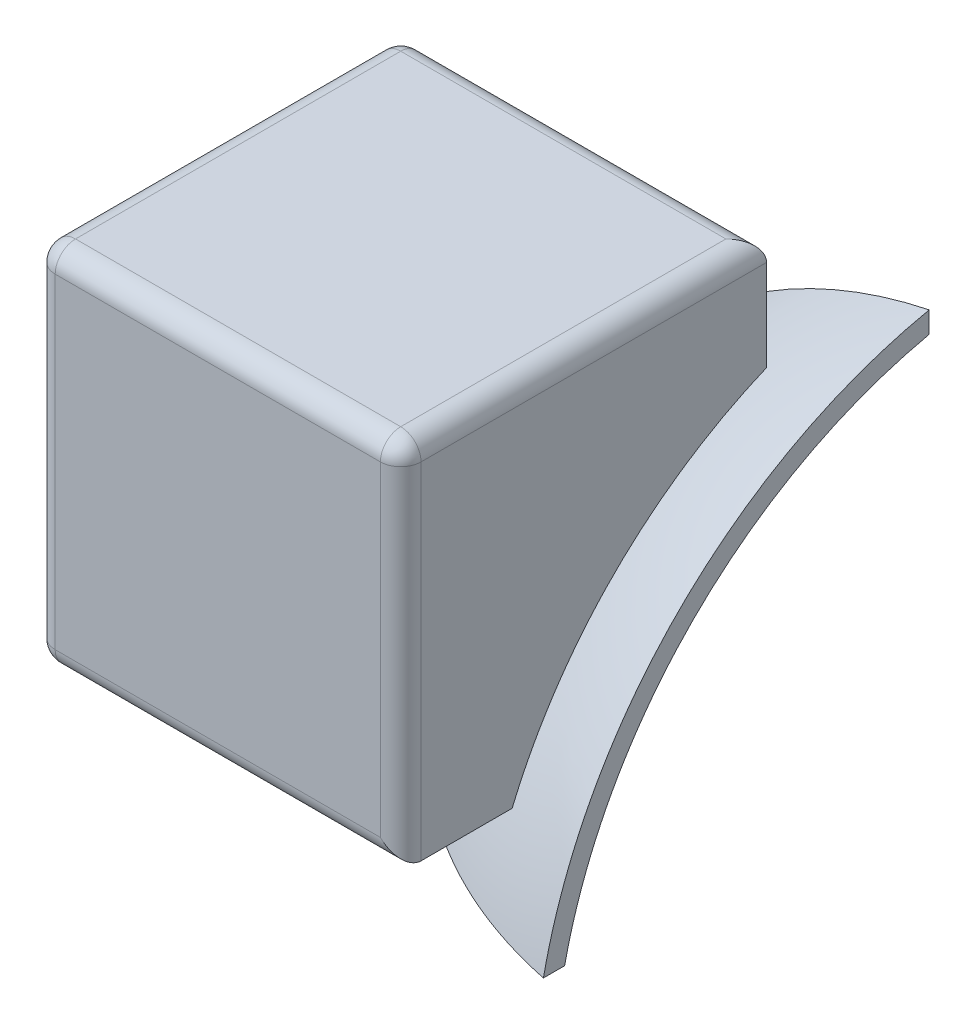
SolidWorks part; units mm, degrees
ref_plane "前视基准面" through (0, 0, 0) normal (0, 0, 1) x (1, 0, 0)
ref_plane "上视基准面" through (0, 0, 0) normal (0, 1, 0) x (1, 0, 0)
ref_plane "右视基准面" through (0, 0, 0) normal (1, 0, 0) x (0, 0, -1)
sketch "草图1" plane through (0, 0, 0) normal (0, 1, 0) x (1, 0, 0)
  line L1 (-27, 27) -> (27, 27)
  line L2 (-27, 27) -> (-27, -27)
  line L3 (-27, -27) -> (27, -27)
  line L4 (27, 27) -> (27, -27)
  line L5 (-27, 27) -> (27, -27) construction
  line L6 (-27, -27) -> (27, 27) construction
  point P0 (0, 0)
  dimension "D1" = 54
  dimension "D2" = 54
extrude "凸台-拉伸1" add sketch "草图1" along normal mid plane 54
ref_plane "基准面1" through (-27, 0, 0) normal (-1, 0, 0) x (0, 0, 1)
sketch "草图2" plane through (-27, 0, 0) normal (-1, 0, 0) x (0, 0, 1)
  line L0 (9, 27) -> (-27, 27)
  line L1 (-27, 27) -> (-27, -27)
  line L2 (-27, -27) -> (27, -27)
  line L3 (27, 9) -> (9, 9)
  line L4 (9, 27) -> (9, 9)
  line L5 (27, -27) -> (27, 9)
  dimension "D1" = 18
  dimension "D2" = 18
extrude "切除-拉伸2" cut sketch "草图2" against normal blind 54
ref_plane "基准面2" through (0, 27, 0) normal (0, 1, 0) x (1, 0, 0)
sketch "草图4" plane through (0, 27, 0) normal (0, 1, 0) x (1, 0, 0)
  line L0 (27, -9) -> (-9, -9)
  line L1 (27, -9) -> (-27, -9) construction
  line L2 (-9, -9) -> (-9, -27)
  line L3 (-27, -27) -> (27, -27) construction
  line L4 (-9, -27) -> (27, -27)
  line L5 (27, -27) -> (27, -9)
  line L6 (-27, 9.9) -> (-27, -9.9) construction
  dimension "D1" = 18
extrude "切除-拉伸3" cut sketch "草图4" against normal through all
fillet "圆角2" radius 1 9 edges at (-27, 18, 27) (-18, 27, 27) (-18, 27, 9) (-9, 27, 18) (-9, 18, 27) (-18, 9, 27) (-27, 9, 18) (-27, 18, 9) (-27, 27, 18)
sketch "草图5" plane through (0, 0, 0) normal (0, 1, 0) x (1, 0, 0)
  line L2 (0, -25) -> (0, 25)
  arc A0 (0, 25) -> (0, -25) centre (0, 0) ccw
  dimension "D1" = 50
revolve "切除-旋转6" cut sketch "草图5" angle 360 about L2
sketch "草图6" plane through (0, 0, 0) normal (0, 1, 0) x (1, 0, 0)
  line L1 (-24, 0) -> (-25, 0)
  line L2 (0, -25) -> (0, -24)
  arc A0 (-25, 0) -> (0, -25) centre (0, 0) ccw
  arc A1 (-24, 0) -> (0, -24) centre (0, 0) ccw
  dimension "D1" = 50
  dimension "D2" = 48
revolve "旋转8" add sketch "草图6" angle 90 about L2
ref_plane "基准面4" through (0, 0, 5) normal (0, 0, 1) x (1, 0, 0)
sketch "草图8" plane through (0, 0, 5) normal (0, 0, 1) x (1, 0, 0)
  line L1 (0.5866, -0.6484) -> (-27.4631, -0.6484)
  line L2 (0.5866, -0.6484) -> (0.5866, 27.3086)
  line L3 (0.5866, 27.3086) -> (-27.4631, 27.3086)
  line L4 (-27.4631, -0.6484) -> (-27.4631, 27.3086)
extrude "切除-拉伸4" cut sketch "草图8" against normal through all
ref_plane "基准面5" through (0, 5, 0) normal (0, 1, 0) x (1, 0, 0)
sketch "草图9" plane through (0, 5, 0) normal (0, 1, 0) x (1, 0, 0)
  line L1 (0.3345, -3.9008) -> (-27.4299, -3.9008)
  line L2 (0.3345, -3.9008) -> (0.3345, -27.4362)
  line L3 (0.3345, -27.4362) -> (-27.4299, -27.4362)
  line L4 (-27.4299, -3.9008) -> (-27.4299, -27.4362)
extrude "切除-拉伸5" cut sketch "草图9" against normal through all
ref_plane "基准面6" through (-5, 0, 0) normal (1, 0, 0) x (0, 0, -1)
sketch "草图10" plane through (-5, 0, 0) normal (1, 0, 0) x (0, 0, -1)
  line L1 (-3.9297, 4.1914) -> (-27.1242, 4.1914)
  line L2 (-3.9297, 4.1914) -> (-3.9297, 27.077)
  line L3 (-3.9297, 27.077) -> (-27.1242, 27.077)
  line L4 (-27.1242, 4.1914) -> (-27.1242, 27.077)
extrude "切除-拉伸6" cut sketch "草图10" along normal blind 54
scale "缩放比例2" bodies to scale 110 115 scale about origin uniform scaling yes scale factor 2.083333
